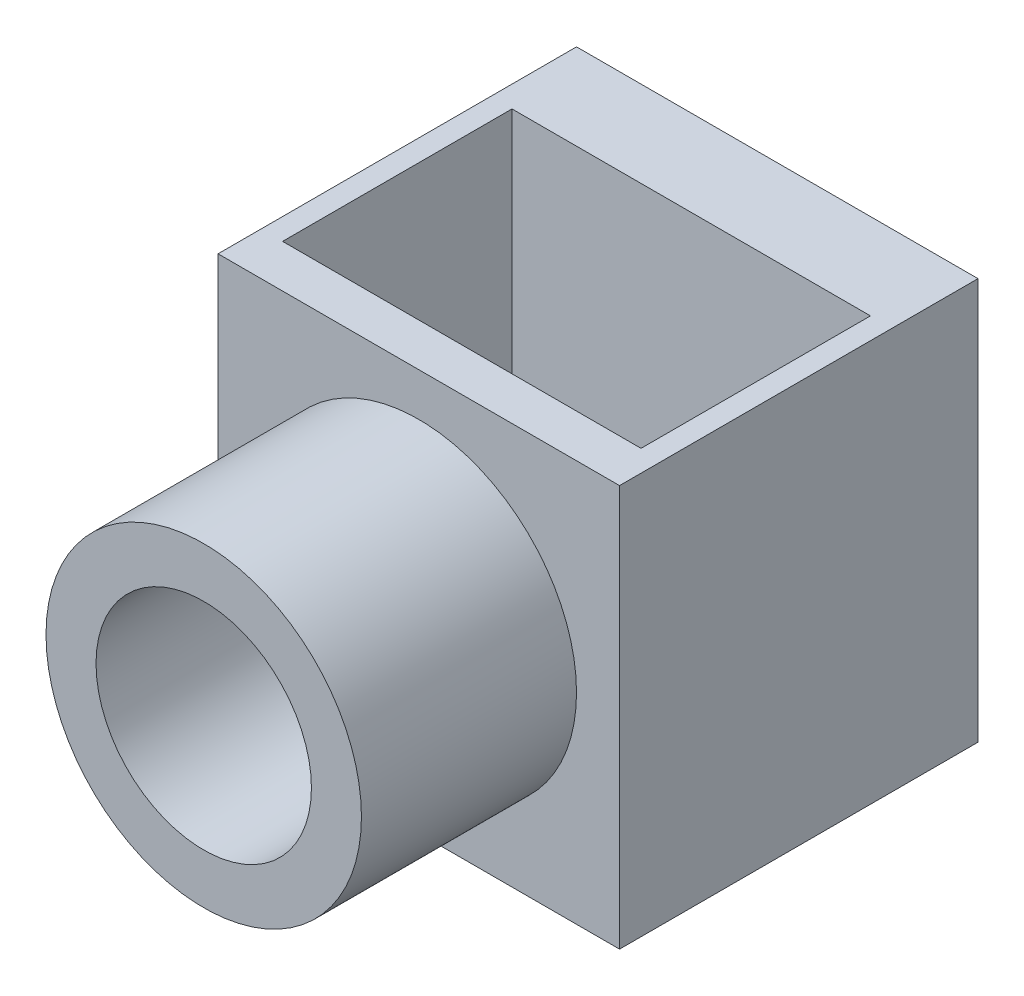
SolidWorks part; units mm, degrees
ref_plane "Front Plane" through (0, 0, 0) normal (0, 0, 1) x (1, 0, 0)
ref_plane "Top Plane" through (0, 0, 0) normal (0, 1, 0) x (1, 0, 0)
ref_plane "Right Plane" through (0, 0, 0) normal (1, 0, 0) x (0, 0, -1)
sketch "Sketch1" plane through (0, 0, 0) normal (0, 1, 0) x (1, 0, 0)
  line L1 (0, 0) -> (7.112, 0)
  line L2 (0, 0) -> (0, 6.35)
  line L3 (0, 6.35) -> (7.112, 6.35)
  line L4 (7.112, 0) -> (7.112, 6.35)
  dimension "D1" = 6.35
  dimension "D2" = 7.112
extrude "Boss-Extrude1" add sketch "Sketch1" along normal blind 7.112
sketch "Sketch2" plane through (0, 0, 0) normal (0, 0, 1) x (1, 0, 0)
  line L0 (0, 7.112) -> (0, 0) construction
  line L1 (0, 0) -> (7.112, 0) construction
  circle A0 centre (3.556, 3.556) radius 2.286
  dimension "D1" = 4.572
  dimension "D2" = 3.556
  dimension "D3" = 3.556
extrude "Cut-Extrude1" cut sketch "Sketch2" against normal blind 1.27
sketch "Sketch3" plane through (0, 7.112, 0) normal (0, 1, 0) x (1, 0, 0)
  line L1 (0.381, 4.826) -> (6.731, 4.826)
  line L2 (0.381, 4.826) -> (0.381, 0.762)
  line L3 (0.381, 0.762) -> (6.731, 0.762)
  line L4 (6.731, 4.826) -> (6.731, 0.762)
  line L5 (7.112, 6.35) -> (0, 6.35) construction
  line L6 (0, 6.35) -> (0, 0) construction
  dimension "D1" = 4.064
  dimension "D2" = 6.35
  dimension "D3" = 0.381
  dimension "D4" = 1.524
extrude "Cut-Extrude2" cut sketch "Sketch3" against normal blind 6.35 contours L2 L1 L4 L3
sketch "Sketch4" plane through (0, 0, 0) normal (0, 0, 1) x (1, 0, 0)
  circle A0 centre (3.556, 3.556) radius 2.794
  circle A1 centre (3.556, 3.556) radius 2.286 construction
  dimension "D1" = 0.508
extrude "Boss-Extrude2" add sketch "Sketch4" along normal blind 3.81 contours A0
sketch "Sketch6" plane through (0, 0, 3.81) normal (0, 0, 1) x (1, 0, 0)
  circle A0 centre (3.556, 3.556) radius 1.908
  circle A1 centre (3.556, 3.556) radius 2.794 construction
extrude "Cut-Extrude3" cut sketch "Sketch6" against normal blind 3.81
